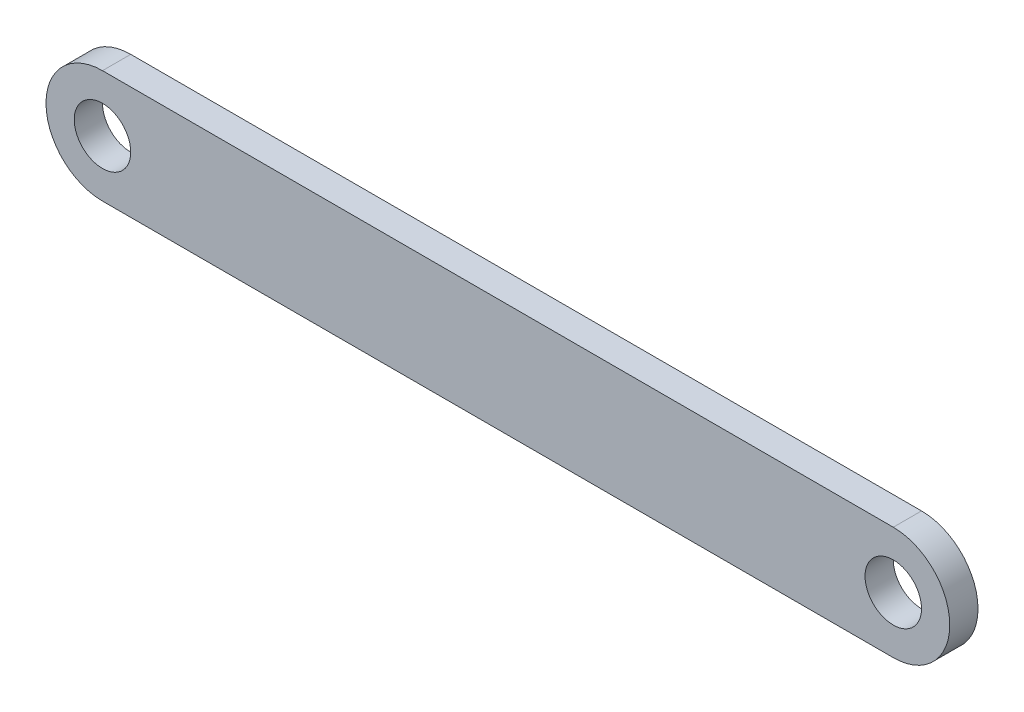
SolidWorks part; units mm, degrees
ref_plane "Alzado" through (0, 0, 0) normal (0, 0, 1) x (1, 0, 0)
ref_plane "Planta" through (0, 0, 0) normal (0, 1, 0) x (1, 0, 0)
ref_plane "Vista lateral" through (0, 0, 0) normal (1, 0, 0) x (0, 0, -1)
sketch "Croquis1" plane through (0, 0, 0) normal (0, 0, 1) x (1, 0, 0)
  line L0 (-70, 0) -> (70, 0) construction
  line L1 (-70, 10) -> (70, 10)
  line L2 (-70, -10) -> (70, -10)
  arc A0 (-70, 10) -> (-70, -10) centre (-70, 0) ccw
  arc A1 (70, -10) -> (70, 10) centre (70, 0) ccw
  circle A2 centre (70, 0) radius 5
  circle A3 centre (-70, 0) radius 5
  point P2 (0, 0)
  dimension "D2" = 10
  dimension "D1" = 140
  dimension "D3" = 20
extrude "Saliente-Extruir1" add sketch "Croquis1" along normal blind 5
equation "\"largo\"= 140"
